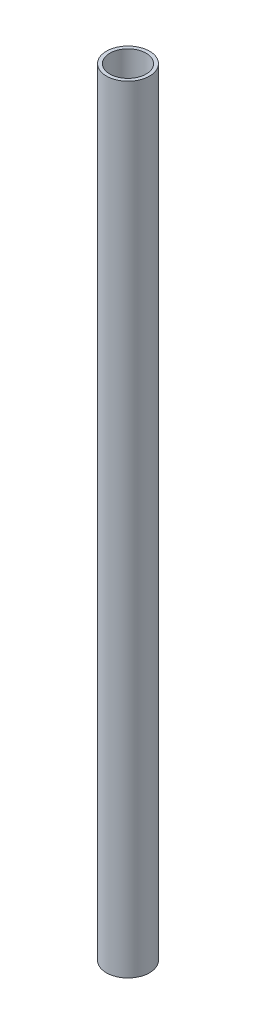
SolidWorks part; units mm, degrees
ref_plane "Alzado" through (0, 0, 0) normal (0, 0, 1) x (1, 0, 0)
ref_plane "Planta" through (0, 0, 0) normal (0, 1, 0) x (1, 0, 0)
ref_plane "Vista lateral" through (0, 0, 0) normal (1, 0, 0) x (0, 0, -1)
sketch "Croquis1" plane through (0, 0, 0) normal (0, 1, 0) x (1, 0, 0)
  circle A0 centre (0, 0) radius 12.5
  circle A1 centre (0, 0) radius 10.5
  dimension "D1" = 25
  dimension "D2" = 2
extrude "Saliente-Extruir1" add sketch "Croquis1" along normal blind 450
